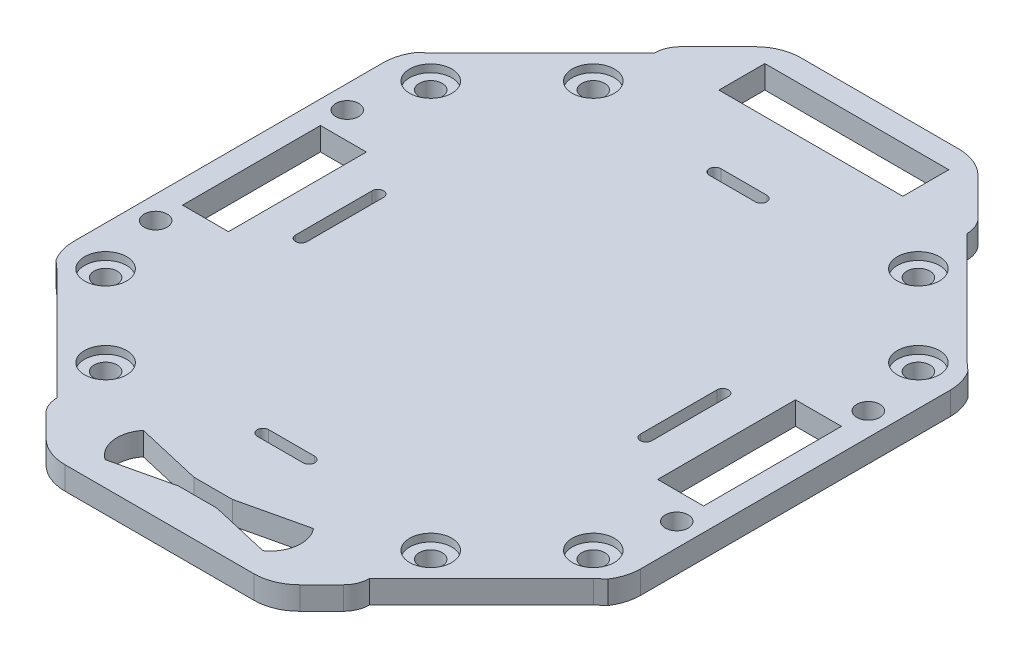
SolidWorks part; units mm, degrees
ref_plane "前视基准面" through (0, 0, 0) normal (0, 0, 1) x (1, 0, 0)
ref_plane "上视基准面" through (0, 0, 0) normal (0, 1, 0) x (1, 0, 0)
ref_plane "右视基准面" through (0, 0, 0) normal (1, 0, 0) x (0, 0, -1)
sketch "草图1" plane through (0, 0, 0) normal (0, 1, 0) x (1, 0, 0)
  line L0 (0, 0) -> (0, 70.7992) construction
  line L1 (0, 0) -> (104.9803, 0) construction
  line L2 (0, 0) -> (-64.2109, 64.2109) construction
  line L3 (-9.176, 43.857) -> (-46.4815, 6.5515) construction
  line L4 (-33.5876, 15.9099) -> (-15.9099, 33.5876) construction
  line L5 (-10.3259, 48) -> (10.3259, 48)
  line L6 (-37, 20.199) -> (-37, -20.199)
  line L7 (-10.3259, -48) -> (10.3259, -48)
  line L8 (37, 20.199) -> (37, -20.199)
  line L11 (-37.1231, 19.4454) -> (-19.4454, 37.1231) construction
  line L12 (-39.2444, 21.5668) -> (-21.5668, 39.2444) construction
  line L13 (-30.4056, 30.4056) -> (-14.5685, 46.2426)
  line L14 (30.4056, 30.4056) -> (14.5685, 46.2426)
  line L15 (-30.4056, -30.4056) -> (-14.5685, -46.2426)
  line L16 (30.4056, -30.4056) -> (14.5685, -46.2426)
  circle A0 centre (-21.2132, 31.8198) radius 1.5
  circle A1 centre (-31.8198, 21.2132) radius 1.5
  circle A2 centre (31.8198, 21.2132) radius 1.5
  circle A3 centre (21.2132, 31.8198) radius 1.5
  circle A4 centre (-31.8198, -21.2132) radius 1.5
  circle A5 centre (-21.2132, -31.8198) radius 1.5
  circle A6 centre (31.8198, -21.2132) radius 1.5
  circle A7 centre (21.2132, -31.8198) radius 1.5
  arc A8 (-37, 20.199) -> (-36.027, 23.4745) centre (-31, 20.199) cw
  arc A9 (-30.4056, 30.4056) -> (-36.027, 23.4745) centre (0, 0) ccw
  arc A10 (-10.3259, 48) -> (-14.5685, 46.2426) centre (-10.3259, 42) ccw
  arc A11 (10.3259, 48) -> (14.5685, 46.2426) centre (10.3259, 42) cw
  arc A12 (30.4056, 30.4056) -> (36.027, 23.4745) centre (0, 0) cw
  arc A13 (37, 20.199) -> (36.027, 23.4745) centre (31, 20.199) ccw
  arc A14 (-10.3259, -48) -> (-14.5685, -46.2426) centre (-10.3259, -42) cw
  arc A15 (-30.4056, -30.4056) -> (-36.027, -23.4745) centre (0, 0) cw
  arc A16 (-37, -20.199) -> (-36.027, -23.4745) centre (-31, -20.199) ccw
  arc A17 (10.3259, -48) -> (14.5685, -46.2426) centre (10.3259, -42) ccw
  arc A18 (30.4056, -30.4056) -> (36.027, -23.4745) centre (0, 0) ccw
  arc A19 (37, -20.199) -> (36.027, -23.4745) centre (31, -20.199) cw
  dimension "D3" = 3
  dimension "D17" = 6
  dimension "D19" = 6
  dimension "D1" = 45
  dimension "D2" = 37.5
  dimension "D4" = 15
  dimension "D5" = 7.5
  dimension "D6" = 20.6518
  dimension "D7" = 74
  dimension "D8" = 2.5
  dimension "D9" = 2.5
  dimension "D10" = 25
  dimension "D11" = 12.5
  dimension "D12" = 25
  dimension "D13" = 12.5
  dimension "D14" = 8
  dimension "D15" = 25
  dimension "D16" = 12.5
  dimension "D18" = 36.027
extrude "凸台-拉伸1" add sketch "草图1" along normal blind 3
sketch "草图2" plane through (0, 3, 0) normal (0, 1, 0) x (1, 0, 0)
  circle A0 centre (-21.2132, 31.8198) radius 2.75
  circle A1 centre (-31.8198, 21.2132) radius 2.75
  circle A2 centre (21.2132, 31.8198) radius 2.75
  circle A3 centre (31.8198, 21.2132) radius 2.75
  circle A4 centre (-31.8198, -21.2132) radius 2.75
  circle A5 centre (-21.2132, -31.8198) radius 2.75
  circle A7 centre (21.2132, -31.8198) radius 2.75
  circle A8 centre (31.8198, -21.2132) radius 2.75
  dimension "D1" = 5.5
extrude "切除-拉伸1" cut sketch "草图2" against normal blind 1
sketch "草图3" plane through (0, 3, 0) normal (0, 1, 0) x (1, 0, 0)
  line L0 (-10.3259, -48) -> (10.3259, -48) construction
  line L1 (-12, -37) -> (12, -37)
  line L2 (-12, -37) -> (-12, -43)
  line L3 (-12, -43) -> (12, -43)
  line L4 (12, -37) -> (12, -43)
  line L5 (-12, -37) -> (12, -43) construction
  line L6 (-12, -43) -> (12, -37) construction
  line L7 (10.3259, 48) -> (-10.3259, 48) construction
  line L8 (-12, 45) -> (12, 45)
  line L9 (-12, 45) -> (-12, 39)
  line L10 (-12, 39) -> (12, 39)
  line L11 (12, 45) -> (12, 39)
  line L12 (-12, 45) -> (12, 39) construction
  line L13 (-12, 39) -> (12, 45) construction
  line L14 (-37, 20.199) -> (-37, -20.199) construction
  line L15 (37, -20.199) -> (37, 20.199) construction
  line L16 (0, 0) -> (45.415, 0) construction
  line L17 (0, 0) -> (0, 53.3677) construction
  line L18 (34, -9) -> (28, -9)
  line L19 (-34, 9) -> (-28, 9)
  line L20 (-34, 9) -> (-34, -9)
  line L21 (-34, -9) -> (-28, -9)
  line L22 (-28, 9) -> (-28, -9)
  line L23 (-34, 9) -> (-28, -9) construction
  line L24 (-34, -9) -> (-28, 9) construction
  line L25 (28, 9) -> (28, -9)
  line L26 (34, 9) -> (28, 9)
  line L27 (34, 9) -> (34, -9)
  circle A0 centre (-34, 12.5) radius 1.5
  circle A1 centre (-34, -12.5) radius 1.5
  circle A2 centre (34, 12.5) radius 1.5
  circle A3 centre (34, -12.5) radius 1.5
  point P0 (0, -40)
  point P9 (0, 42)
  point P25 (-31, 0)
  dimension "D7" = 3
  dimension "D1" = 6
  dimension "D2" = 24
  dimension "D3" = 5
  dimension "D4" = 24
  dimension "D5" = 6
  dimension "D6" = 3
  dimension "D8" = 3
  dimension "D9" = 3
  dimension "D10" = 25
  dimension "D11" = 12.5
  dimension "D12" = 6
  dimension "D13" = 18
  dimension "D14" = 3
extrude "切除-拉伸2" cut sketch "草图3" against normal blind 10
sketch "草图4" plane through (0, 0, 0) normal (0, -1, 0) x (1, 0, 0)
  line L0 (0, 0) -> (0, 54.2429) construction
  line L1 (-8, 46) -> (8, 46) construction
  line L2 (-10.3259, 48) -> (10.3259, 48) construction
  line L3 (-10.3259, 48) -> (10.3259, 48) construction
  line L4 (10.3259, 48) -> (10.3259, 49) construction
  line L5 (10.3259, 49) -> (-10.3259, 49) construction
  line L6 (-10.3259, 49) -> (-10.3259, 48) construction
  line L7 (-12.3259, 46) -> (12.3259, 46)
  line L8 (14.5685, 46.2426) -> (30.4056, 30.4056) construction
  line L9 (-30.4056, 30.4056) -> (-14.5685, 46.2426) construction
  line L10 (16.5685, 44.2426) -> (30.4056, 30.4056) construction
  line L11 (-30.4056, 30.4056) -> (-16.5685, 44.2426) construction
  line L12 (-16.5685, 44.2426) -> (-16.5685, 49)
  line L13 (-16.5685, 49) -> (16.5685, 49)
  line L14 (16.5685, 49) -> (16.5685, 44.2426)
  arc A0 (-10.3259, 48) -> (-14.5685, 46.2426) centre (-10.3259, 42) ccw construction
  arc A1 (-10.3259, 48) -> (-14.5685, 46.2426) centre (-10.3259, 42) ccw construction
  arc A2 (14.5685, 46.2426) -> (10.3259, 48) centre (10.3259, 42) ccw construction
  arc A3 (14.5685, 46.2426) -> (10.3259, 48) centre (10.3259, 42) ccw construction
  arc A4 (10.3259, 48) -> (9, 46.8599) centre (10.3259, 46.659) ccw construction
  arc A5 (9, 46.8599) -> (8, 46) centre (8, 47.0114) cw construction
  arc A6 (-9, 46.8599) -> (-8, 46) centre (-8, 47.0114) ccw construction
  arc A7 (-10.3259, 48) -> (-9, 46.8599) centre (-10.3259, 46.659) cw construction
  arc A8 (16.5685, 44.2426) -> (12.3259, 46) centre (12.3259, 40) ccw
  arc A9 (-12.3259, 46) -> (-16.5685, 44.2426) centre (-12.3259, 40) ccw
  dimension "D5" = 6
  dimension "D1" = 2
  dimension "D2" = 16
  dimension "D3" = 1
  dimension "D4" = 18
  dimension "D6" = 3
extrude "切除-拉伸3" cut sketch "草图4" against normal blind 10
sketch "草图5" plane through (0, 0, 0) normal (0, -1, 0) x (1, 0, 0)
  line L0 (-12, 37) -> (12, 37) construction
  line L1 (12, 37) -> (12, 43) construction
  line L2 (-12, 43) -> (-12, 37) construction
  line L3 (12, 43) -> (-12, 43) construction
  line L4 (-12, 37) -> (12, 37) construction
  line L5 (12, 37) -> (12, 43) construction
  line L6 (-12, 43) -> (-12, 37) construction
  line L7 (12, 43) -> (-12, 43) construction
  line L8 (-10.3, 42.8081) -> (-2.5, 41)
  line L9 (-2.5, 41) -> (2.5, 41)
  line L10 (2.5, 41) -> (10.3, 42.8081)
  line L11 (-12, 40) -> (12, 40) construction
  line L12 (0, 43) -> (0, 37) construction
  line L13 (2.5, 39) -> (11.1, 37.0076)
  line L14 (-2.5, 39) -> (2.5, 39)
  line L15 (-11.1, 37.0076) -> (-2.5, 39)
  line L16 (-12, 37) -> (-12, 36)
  line L17 (-12, 36) -> (12, 36)
  line L18 (12, 36) -> (12, 37)
  line L19 (-12, 43) -> (-12, 44)
  line L20 (-12, 44) -> (12, 44)
  line L21 (12, 44) -> (12, 43)
  line L22 (-12, 43) -> (-13, 43)
  line L24 (-13, 43) -> (-13, 37)
  line L25 (-13, 37) -> (-12, 37)
  line L26 (12, 43) -> (13, 43)
  line L27 (13, 43) -> (13, 37)
  line L28 (13, 37) -> (12, 37)
  arc A0 (-10.3, 42.8081) -> (-11.1, 37.0076) centre (-8, 39.5355) ccw
  arc A1 (10.3, 42.8081) -> (11.1, 37.0076) centre (8, 39.5355) cw
  dimension "D6" = 4
  dimension "D2" = 5
  dimension "D3" = 2.5
  dimension "D4" = 1
  dimension "D5" = 1
  dimension "D7" = 7.8
  dimension "D8" = 2.8081
  dimension "D9" = 8.6
  dimension "D10" = 7.8
  dimension "D11" = 8.6
  dimension "D12" = 1
  dimension "D13" = 1
  dimension "D14" = 2
extrude "凸台-拉伸2" add sketch "草图5" against normal blind 3
sketch "草图6" plane through (0, 0, 0) normal (0, -1, 0) x (1, 0, 0)
  line L0 (-22.5, 5) -> (-22.5, -5) construction
  line L1 (-19.5, 26.5) -> (19.5, 26.5) construction
  line L2 (-19.5, 26.5) -> (-19.5, -26.5) construction
  line L3 (-19.5, -26.5) -> (19.5, -26.5) construction
  line L4 (19.5, 26.5) -> (19.5, -26.5) construction
  line L5 (-19.5, 26.5) -> (19.5, -26.5) construction
  line L6 (-19.5, -26.5) -> (19.5, 26.5) construction
  line L11 (-21.75, 5) -> (-21.75, -5)
  line L12 (-23.25, 5) -> (-23.25, -5)
  line L13 (-3, 29.5) -> (3, 29.5) construction
  line L14 (-3, 30.25) -> (3, 30.25)
  line L15 (-3, 28.75) -> (3, 28.75)
  line L16 (0, 0) -> (0, 15.348) construction
  line L17 (0, 0) -> (11.1231, 0) construction
  line L18 (-3, -29.5) -> (3, -29.5) construction
  line L19 (-3, -30.25) -> (3, -30.25)
  line L20 (-3, -28.75) -> (3, -28.75)
  line L21 (22.5, 5) -> (22.5, -5) construction
  line L22 (21.75, 5) -> (21.75, -5)
  line L23 (23.25, 5) -> (23.25, -5)
  arc A0 (-21.75, 5) -> (-23.25, 5) centre (-22.5, 5) ccw
  arc A1 (-23.25, -5) -> (-21.75, -5) centre (-22.5, -5) ccw
  arc A2 (-3, 30.25) -> (-3, 28.75) centre (-3, 29.5) ccw
  arc A3 (3, 28.75) -> (3, 30.25) centre (3, 29.5) ccw
  arc A4 (-3, -30.25) -> (-3, -28.75) centre (-3, -29.5) cw
  arc A5 (3, -28.75) -> (3, -30.25) centre (3, -29.5) cw
  arc A6 (21.75, 5) -> (23.25, 5) centre (22.5, 5) cw
  arc A7 (23.25, -5) -> (21.75, -5) centre (22.5, -5) cw
  point P0 (0, 0)
  point P8 (-22.5, 0)
  point P13 (0, 29.5)
  point P33 (0, -29.5)
  point P40 (22.5, 0)
  dimension "D1" = 39
  dimension "D2" = 53
  dimension "D3" = 1.5
  dimension "D4" = 1.5
  dimension "D5" = 10
  dimension "D6" = 6
  dimension "D7" = 3
  dimension "D8" = 3
extrude "切除-拉伸4" cut sketch "草图6" against normal blind 3
sketch "草图7" plane through (0, 0, 0) normal (0, -1, 0) x (1, 0, 0)
  line L1 (-31.8198, 21.2132) -> (-21.2132, 31.8198) construction
  line L2 (-20.397, 39) -> (-35.0018, 24.3952)
  line L3 (-30.4056, 30.4056) -> (-16.5685, 44.2426) construction
  line L4 (-31.8198, 21.2132) -> (-35.0018, 24.3952) construction
  line L5 (-26.5165, 26.5165) -> (-33.6912, 33.6912) construction
  line L6 (-35.0018, 24.3952) -> (-36.027, 23.4745)
  line L8 (-20.9952, 43.0125) -> (-38.2801, 25.7276)
  line L10 (-38.2801, 25.7276) -> (-36.027, 23.4745)
  line L14 (0, 0) -> (0, 50.5043) construction
  line L16 (0, 0) -> (48.6005, 0) construction
  line L32 (-20.9952, 43.0125) -> (-19.397, 41.4142)
  line L33 (38.2801, 25.7276) -> (36.027, 23.4745)
  line L34 (35.0018, 24.3952) -> (36.027, 23.4745)
  line L35 (20.397, 39) -> (35.0018, 24.3952)
  line L36 (20.9952, 43.0125) -> (19.397, 41.4142)
  line L37 (20.9952, 43.0125) -> (38.2801, 25.7276)
  line L38 (35.0018, -24.3952) -> (36.027, -23.4745)
  line L39 (38.2801, -25.7276) -> (36.027, -23.4745)
  line L40 (20.397, -39) -> (35.0018, -24.3952)
  line L41 (20.9952, -43.0125) -> (19.397, -41.4142)
  line L42 (20.9952, -43.0125) -> (38.2801, -25.7276)
  line L43 (-20.9952, -43.0125) -> (-38.2801, -25.7276)
  line L44 (-20.9952, -43.0125) -> (-19.397, -41.4142)
  line L45 (-20.397, -39) -> (-35.0018, -24.3952)
  line L46 (-35.0018, -24.3952) -> (-36.027, -23.4745)
  line L47 (-38.2801, -25.7276) -> (-36.027, -23.4745)
  circle A3 centre (-31.8198, 21.2132) radius 1.5 construction
  circle A4 centre (-21.2132, 31.8198) radius 1.5 construction
  circle A5 centre (-31.8198, 21.2132) radius 1.5 construction
  circle A6 centre (-21.2132, 31.8198) radius 1.5 construction
  arc A12 (-20.397, 39) -> (-19.397, 41.4142) centre (-16.9828, 39) cw
  arc A13 (20.397, 39) -> (19.397, 41.4142) centre (16.9828, 39) ccw
  arc A14 (20.397, -39) -> (19.397, -41.4142) centre (16.9828, -39) cw
  arc A15 (-20.397, -39) -> (-19.397, -41.4142) centre (-16.9828, -39) ccw
  dimension "D1" = 4.5
extrude "切除-拉伸5" cut sketch "草图7" against normal blind 10
